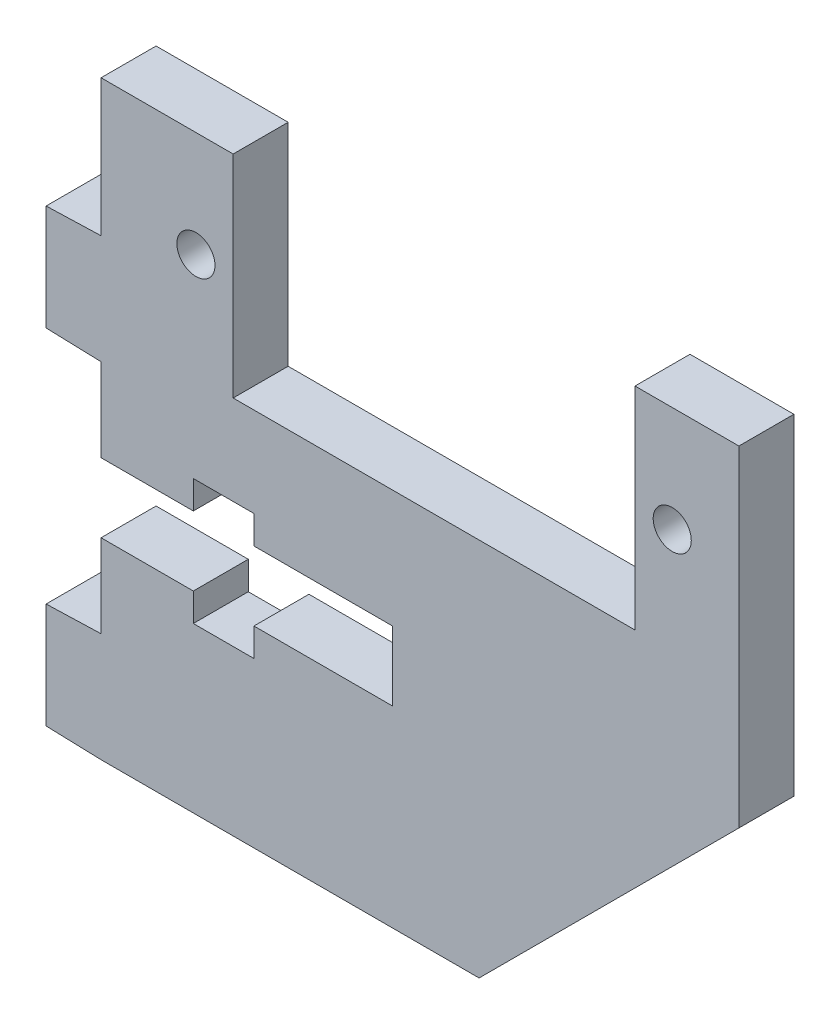
SolidWorks part; units mm, degrees
ref_plane "Front Plane" through (0, 0, 0) normal (0, 0, 1) x (1, 0, 0)
ref_plane "Top Plane" through (0, 0, 0) normal (0, 1, 0) x (1, 0, 0)
ref_plane "Right Plane" through (0, 0, 0) normal (1, 0, 0) x (0, 0, -1)
sketch "Sketch1" plane through (0, 0, 0) normal (0, 0, 1) x (1, 0, 0)
  line L0 (10.8, 34) -> (10.8, 21.8)
  line L1 (0, 0) -> (40, 0)
  line L2 (0, 0) -> (0, 6.1)
  line L3 (3.175, 34) -> (10.8, 34)
  line L4 (40, 0) -> (40, 34)
  line L5 (10.8, 21.8) -> (34, 21.8)
  line L6 (34, 21.8) -> (34, 34)
  line L7 (34, 34) -> (40, 34)
  line L8 (-11.825, 17) -> (40, 17) construction
  line L9 (0, 19.9) -> (3.175, 19.9)
  line L10 (12, 15) -> (20, 15)
  line L11 (0, 6.1) -> (3.175, 6.1)
  line L12 (3.175, 19.9) -> (3.175, 15)
  line L13 (3.175, 15) -> (8.5, 15)
  line L14 (8.5, 11) -> (8.5, 9.375)
  line L15 (3.175, 11) -> (8.5, 11)
  line L16 (20, 15) -> (20, 11)
  line L17 (8.5, 16.625) -> (12, 16.625)
  line L18 (8.5, 16.625) -> (8.5, 15)
  line L19 (8.5, 9.375) -> (12, 9.375)
  line L20 (12, 16.625) -> (12, 15)
  line L21 (3.175, 11) -> (3.175, 6.1)
  line L22 (12, 11) -> (12, 9.375)
  line L23 (0, 19.9) -> (0, 26)
  line L24 (12, 11) -> (20, 11)
  line L25 (0, 26) -> (3.175, 26.1)
  line L26 (0, 26) -> (3.175, 26)
  line L27 (0, 26) -> (0, 34)
  line L28 (0, 34) -> (3.175, 34)
  line L29 (3.175, 26) -> (3.175, 34)
  line L30 (0, 19.9) -> (3.175, 19.8)
  line L31 (0, 6.1) -> (3.175, 6.2)
  line L32 (3.175, -0.1) -> (0, 0)
  line L33 (0, 0) -> (40, 0)
  line L34 (0, 0) -> (0, -0.1)
  line L35 (0, -0.1) -> (40, -0.1)
  line L36 (40, 0) -> (40, -0.1)
  line L37 (0, 0) -> (-0.0051, 0.0038)
  circle A0 centre (8.65, 27.9) radius 1.1
  circle A1 centre (36.15, 27.9) radius 1.1
  dimension "D8" = 2.2
  dimension "D9" = 2.2
  dimension "D1" = 34
  dimension "D2" = 40
  dimension "D3" = 12.2
  dimension "D4" = 23.2
  dimension "D5" = 6
  dimension "D6" = 27.5
  dimension "D7" = 6.1
  dimension "D10" = 2.15
  dimension "D11" = 19.9
  dimension "D12" = 6.1
  dimension "D13" = 3.175
  dimension "D14" = 4
  dimension "D15" = 7.25
  dimension "D16" = 15
  dimension "D17" = 16.625
  dimension "D18" = 3.5
  dimension "D19" = 20
  dimension "D20" = 8.5
  dimension "D21" = 6.1
  dimension "D22" = 3.175
  dimension "D23" = 0.1
  dimension "D24" = 0.1
  dimension "D25" = 0.1
  dimension "D26" = 0.1
extrude "Boss-Extrude1" add sketch "Sketch1" along normal blind 3.175 contours L12 L8 L4 L7 L6 L5 L0 L3 L29 L26 L23 L9 A0 A1 | L8 L12 L13 L18 L17 L20 L10 L16 L24 L22 L19 L14 L15 L21 L11 L2 L1 L4 | L26 L29 L25 | L9 L30 L12 | L31 L11 L21 | L36 L1 L32 L35
chamfer "Chamfer1" distance 15 angle 45 1 edges at (40, -0.1, 1.5875)
